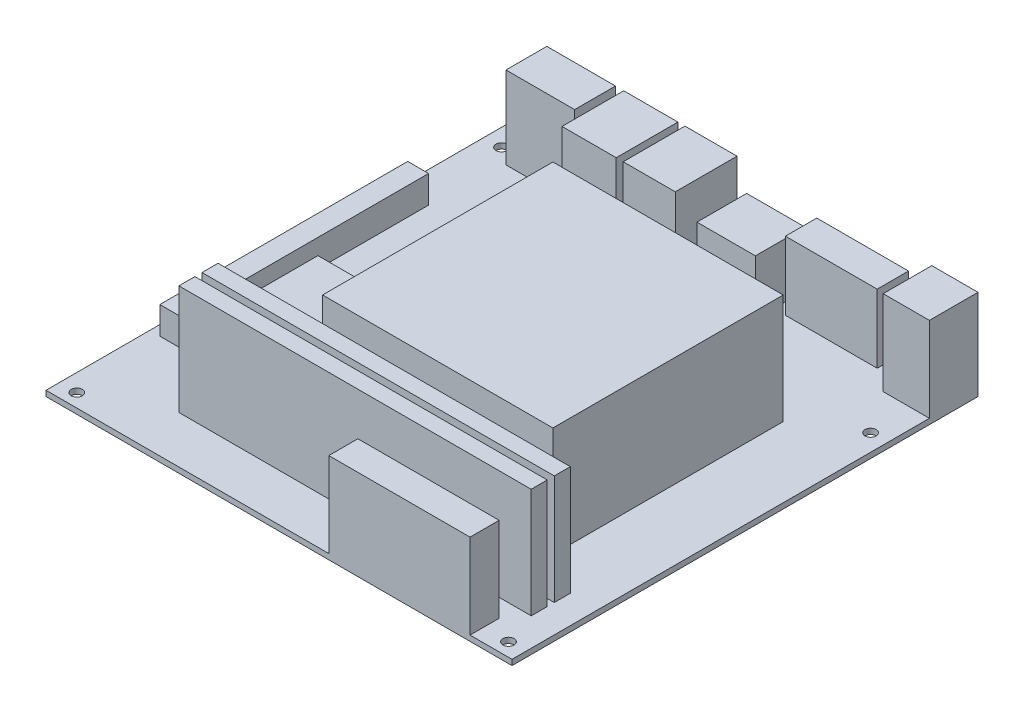
SolidWorks part; units mm, degrees
ref_plane "Front Plane" through (0, 0, 0) normal (0, 0, 1) x (1, 0, 0)
ref_plane "Top Plane" through (0, 0, 0) normal (0, 1, 0) x (1, 0, 0)
ref_plane "Right Plane" through (0, 0, 0) normal (1, 0, 0) x (0, 0, -1)
sketch "Sketch1" plane through (0, 0, 0) normal (0, 1, 0) x (1, 0, 0)
  line L1 (-85, 85) -> (85, 85)
  line L2 (-85, 85) -> (-85, -85)
  line L3 (-85, -85) -> (85, -85)
  line L4 (85, 85) -> (85, -85)
  line L5 (-85, 85) -> (85, -85) construction
  line L6 (-85, -85) -> (85, 85) construction
  point P0 (0, 0)
  dimension "D1" = 170
extrude "Boss-Extrude1" add sketch "Sketch1" along normal blind 2
sketch "Sketch2" plane through (0, 2, 0) normal (0, 1, 0) x (1, 0, 0)
  line L1 (74.7693, -53.496) -> (-53.7497, -53.496)
  line L2 (74.7693, -53.496) -> (74.7693, -59.3494)
  line L3 (74.7693, -59.3494) -> (-53.7497, -59.3494)
  line L4 (-53.7497, -53.496) -> (-53.7497, -59.3494)
  line L5 (74.7693, -61.9159) -> (-53.7497, -61.9159)
  line L6 (74.7693, -61.9159) -> (74.7693, -67.7693)
  line L7 (74.7693, -67.7693) -> (-53.7497, -67.7693)
  line L8 (-53.7497, -61.9159) -> (-53.7497, -67.7693)
extrude "Boss-Extrude2" add sketch "Sketch2" along normal blind 40
sketch "Sketch3" plane through (0, 2, 0) normal (0, 1, 0) x (1, 0, 0)
  line L1 (59.3669, 39.5776) -> (-24.6567, 39.5776)
  line L2 (59.3669, 39.5776) -> (59.3669, -44.446)
  line L3 (59.3669, -44.446) -> (-24.6567, -44.446)
  line L4 (-24.6567, 39.5776) -> (-24.6567, -44.446)
extrude "Boss-Extrude3" add sketch "Sketch3" along normal blind 40
sketch "Sketch4" plane through (0, 2, 0) normal (0, 1, 0) x (1, 0, 0)
  line L0 (85, 85) -> (-85, 85) construction
  line L1 (-47.249, 85) -> (-72.2965, 85)
  line L2 (-47.249, 85) -> (-47.249, 70.0969)
  line L3 (-47.249, 70.0969) -> (-72.2965, 70.0969)
  line L4 (-72.2965, 85) -> (-72.2965, 70.0969)
  line L6 (-44.2358, 85) -> (-24.4695, 85)
  line L7 (-44.2358, 85) -> (-44.2358, 62.4828)
  line L8 (-44.2358, 62.4828) -> (-24.4695, 62.4828)
  line L9 (-24.4695, 85) -> (-24.4695, 62.4828)
  line L10 (-21.907, 85) -> (-2.9146, 85)
  line L11 (-21.907, 85) -> (-21.907, 62.4828)
  line L12 (-21.907, 62.4828) -> (-2.9146, 62.4828)
  line L13 (-2.9146, 85) -> (-2.9146, 62.4828)
extrude "Boss-Extrude4" add sketch "Sketch4" along normal blind 30
sketch "Sketch5" plane through (0, 2, 0) normal (0, 1, 0) x (1, 0, 0)
  line L0 (85, 85) -> (-2.9146, 85) construction
  line L1 (0.6248, 85) -> (21.926, 85)
  line L2 (0.6248, 85) -> (0.6248, 66.8648)
  line L3 (0.6248, 66.8648) -> (21.926, 66.8648)
  line L4 (21.926, 85) -> (21.926, 66.8648)
extrude "Boss-Extrude5" add sketch "Sketch5" along normal blind 20
sketch "Sketch6" plane through (0, 2, 0) normal (0, 1, 0) x (1, 0, 0)
  line L1 (26.1862, 85) -> (59.6595, 85)
  line L2 (26.1862, 85) -> (26.1862, 73.5595)
  line L3 (26.1862, 73.5595) -> (59.6595, 73.5595)
  line L4 (59.6595, 85) -> (59.6595, 73.5595)
  line L5 (85, 85) -> (21.926, 85) construction
extrude "Boss-Extrude6" add sketch "Sketch6" along normal blind 25
sketch "Sketch7" plane through (0, 2, 0) normal (0, 1, 0) x (1, 0, 0)
  line L0 (-85, -85) -> (85, -85) construction
  line L1 (68.1415, 85) -> (85, 85)
  line L2 (68.1415, 85) -> (68.1415, 67.2694)
  line L3 (68.1415, 67.2694) -> (85, 67.2694)
  line L4 (85, 85) -> (85, 67.2694)
  line L5 (69.6931, -74.3815) -> (18.1637, -74.3815)
  line L6 (69.6931, -74.3815) -> (69.6931, -85)
  line L7 (69.6931, -85) -> (18.1637, -85)
  line L8 (18.1637, -74.3815) -> (18.1637, -85)
  line L9 (85, 85) -> (59.6595, 85) construction
extrude "Boss-Extrude7" add sketch "Sketch7" along normal blind 30.95
sketch "Sketch8" plane through (0, 2, 0) normal (0, 1, 0) x (1, 0, 0)
  line L1 (-30.4144, -2.8686) -> (-67.9348, -2.8686)
  line L2 (-30.4144, -2.8686) -> (-30.4144, -37.4082)
  line L3 (-30.4144, -37.4082) -> (-67.9348, -37.4082)
  line L4 (-67.9348, -2.8686) -> (-67.9348, -37.4082)
  line L5 (-73.7069, 43.2766) -> (-81.3236, 43.2766)
  line L6 (-73.7069, 43.2766) -> (-73.7069, -47.1503)
  line L7 (-73.7069, -47.1503) -> (-81.3236, -47.1503)
  line L8 (-81.3236, 43.2766) -> (-81.3236, -47.1503)
extrude "Boss-Extrude8" add sketch "Sketch8" along normal blind 10
sketch "Sketch9" plane through (0, 2, 0) normal (0, 1, 0) x (1, 0, 0)
  line L0 (-72.2965, 85) -> (-85, 85) construction
  line L1 (-85, 85) -> (-85, -85) construction
  circle A0 centre (-78.65, 74.84) radius 2.032
  circle A1 centre (78.83, 51.98) radius 2.032
  circle A2 centre (78.83, -80.1) radius 2.032
  circle A3 centre (-78.65, -80.1) radius 2.032
  dimension "D1" = 4.064
  dimension "D2" = 10.16
  dimension "D3" = 6.35
  dimension "D4" = 154.94
  dimension "D5" = 157.48
  dimension "D6" = 22.86
extrude "Cut-Extrude1" cut sketch "Sketch9" against normal blind 10
